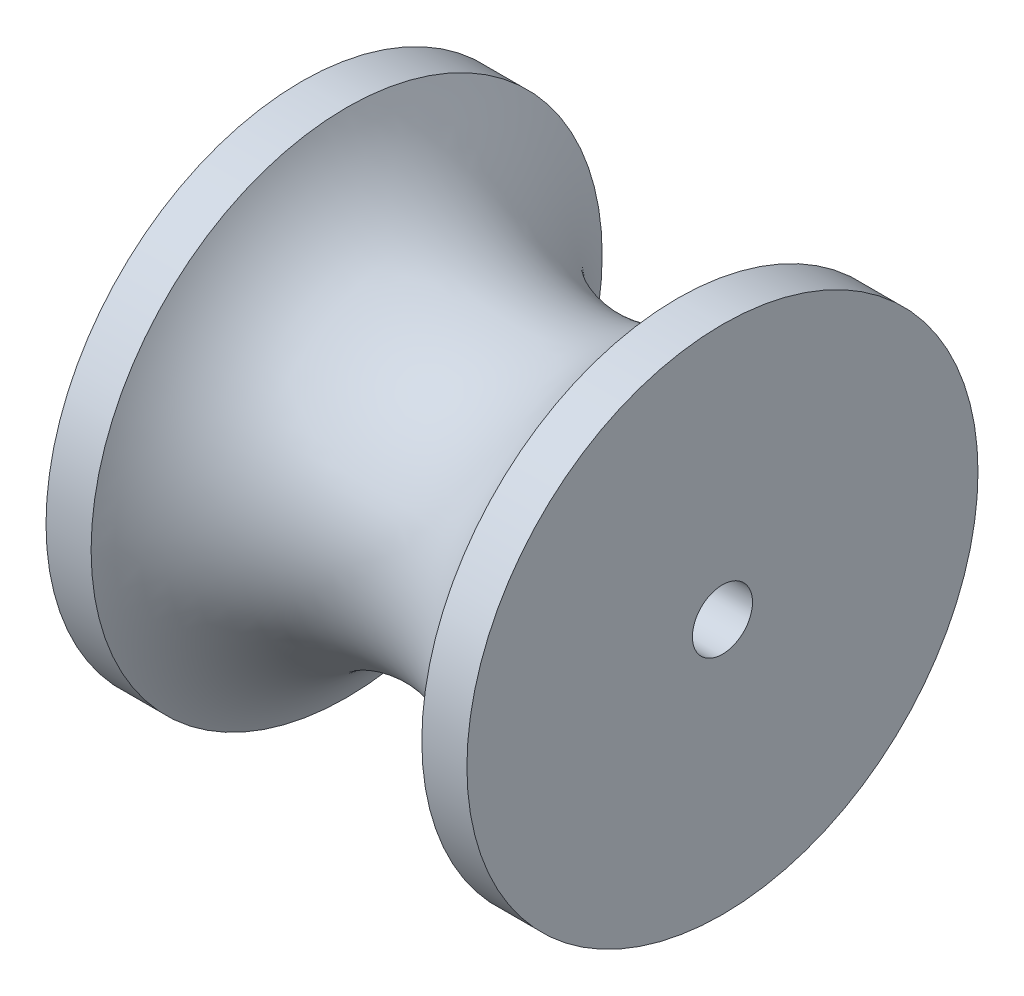
SolidWorks part; units mm, degrees
ref_plane "前视基准面" through (0, 0, 0) normal (0, 0, 1) x (1, 0, 0)
ref_plane "上视基准面" through (0, 0, 0) normal (0, 1, 0) x (1, 0, 0)
ref_plane "右视基准面" through (0, 0, 0) normal (1, 0, 0) x (0, 0, -1)
other "Configuration Table"
sketch "草图1" plane through (0, 0, 0) normal (0, 0, 1) x (1, 0, 0)
  line L0 (250.984, 108.0541) -> (264.984, 108.0541)
  line L1 (250.984, 108.0541) -> (250.984, 116.5541)
  line L2 (264.984, 108.0541) -> (264.984, 116.5541)
  line L3 (250.984, 116.5541) -> (252.484, 116.5541)
  line L4 (264.984, 116.5541) -> (263.484, 116.5541)
  arc A1 (252.484, 116.5541) -> (263.484, 116.5541) centre (257.984, 119.1403) ccw
  dimension "D1" = 14
  dimension "D2" = 8.5
  dimension "D3" = 1.5
  dimension "D4" = 1.5
revolve "旋转1" add sketch "草图1" angle 360 about L0
sketch "草图2" plane through (264.984, 0, 0) normal (1, 0, 0) x (0, 0, -1)
  circle A0 centre (0, 108.0541) radius 1
  dimension "D1" = 2
extrude "切除-拉伸1" cut sketch "草图2" against normal through all
